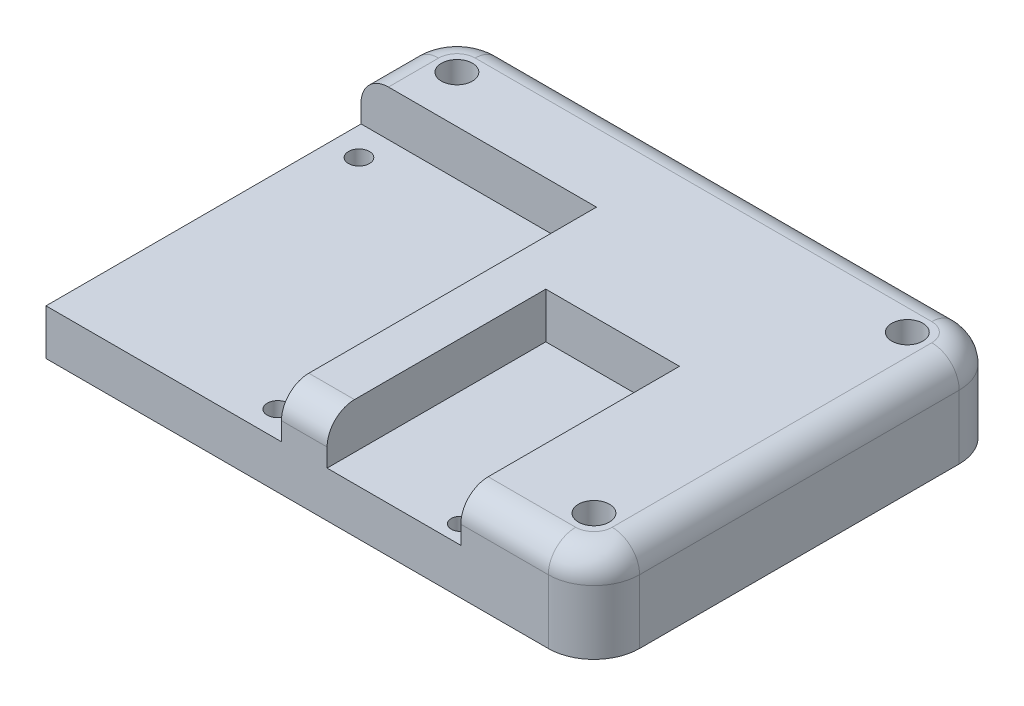
SolidWorks part; units mm, degrees
ref_plane "Front Plane" through (0, 0, 0) normal (0, 0, 1) x (1, 0, 0)
ref_plane "Top Plane" through (0, 0, 0) normal (0, 1, 0) x (1, 0, 0)
ref_plane "Right Plane" through (0, 0, 0) normal (1, 0, 0) x (0, 0, -1)
sketch "Sketch1" plane through (0, 0, 0) normal (0, 1, 0) x (1, 0, 0)
  line L1 (-39.1304, 20.7391) -> (20.8696, 20.7391)
  line L2 (-39.1304, 20.7391) -> (-39.1304, -24.2609)
  line L3 (-39.1304, -24.2609) -> (20.8696, -24.2609)
  line L4 (20.8696, 20.7391) -> (20.8696, -24.2609)
  dimension "D1" = 45
  dimension "D2" = 60
extrude "Boss-Extrude1" add sketch "Sketch1" along normal blind 10
sketch "Sketch2" plane through (0, 10, 0) normal (0, 1, 0) x (1, 0, 0)
  line L0 (-39.1304, -24.2609) -> (20.8696, -24.2609) construction
  line L1 (-13.3504, -24.2609) -> (-39.1304, -24.2609)
  line L2 (-13.3504, -24.2609) -> (-13.3504, 10.2391)
  line L3 (-13.3504, 10.2391) -> (-39.1304, 10.2391)
  line L4 (-39.1304, -24.2609) -> (-39.1304, 10.2391)
  line L5 (-39.1304, 20.7391) -> (-39.1304, -24.2609) construction
  dimension "D1" = 34.5
  dimension "D2" = 25.78
extrude "Cut-Extrude1" cut sketch "Sketch2" against normal blind 5
sketch "Sketch3" plane through (0, 5, 0) normal (0, 1, 0) x (1, 0, 0)
  line L0 (-13.3504, -24.2609) -> (-13.3504, 10.2391) construction
  line L1 (-39.1304, 10.2391) -> (-39.1304, -24.2609) construction
  line L2 (-39.1304, -24.2609) -> (-13.3504, -24.2609) construction
  line L3 (-13.3504, 10.2391) -> (-39.1304, 10.2391) construction
  circle A0 centre (-36.0604, 6.9391) radius 1.15
  circle A1 centre (-16.6404, -21.3709) radius 1.15
  dimension "D1" = 2.3
  dimension "D2" = 2.3
  dimension "D3" = 3.29
  dimension "D4" = 3.07
  dimension "D5" = 2.89
  dimension "D6" = 3.3
extrude "Cut-Extrude2" cut sketch "Sketch3" against normal up to next
sketch "Sketch4" plane through (0, 10, 0) normal (0, 1, 0) x (1, 0, 0)
  line L0 (-13.3504, -24.2609) -> (20.8696, -24.2609) construction
  line L1 (-8.3504, -24.2609) -> (6.2896, -24.2609)
  line L2 (-8.3504, -24.2609) -> (-8.3504, -0.3109)
  line L3 (-8.3504, -0.3109) -> (6.2896, -0.3109)
  line L4 (6.2896, -24.2609) -> (6.2896, -0.3109)
  line L5 (-13.3504, -24.2609) -> (-13.3504, 10.2391) construction
  dimension "D1" = 14.64
  dimension "D2" = 23.95
  dimension "D3" = 5
extrude "Cut-Extrude3" cut sketch "Sketch4" against normal blind 5
sketch "Sketch5" plane through (0, 5, 0) normal (0, 1, 0) x (1, 0, 0)
  line L0 (6.2896, -24.2609) -> (6.2896, -0.3109) construction
  line L1 (-8.3504, -24.2609) -> (6.2896, -24.2609) construction
  line L2 (6.2896, -0.3109) -> (-8.3504, -0.3109) construction
  circle A0 centre (4.2446, -2.3309) radius 1.015
  circle A1 centre (4.2396, -22.2459) radius 1.015
  point P4 (0, 0)
  dimension "D1" = 2.03
  dimension "D2" = 2.03
  dimension "D3" = 2.045
  dimension "D4" = 2.05
  dimension "D5" = 2.015
  dimension "D6" = 2.02
extrude "Cut-Extrude4" cut sketch "Sketch5" against normal up to next
fillet "Fillet1" radius 5 1 edges at (-39.1304, 5, -20.7391)
fillet "Fillet2" radius 5 1 edges at (20.8696, 5, -20.7391)
fillet "Fillet3" radius 5 1 edges at (20.8696, 5, 24.2609)
fillet "Fillet4" radius 3 8 edges at (-10.8504, 10, 24.2609) (-39.1304, 10, -12.9891) (-37.666, 10, -19.2747) (-9.1304, 10, -20.7391) (19.4051, 10, -19.2747) (20.8696, 10, 1.7609) (19.4051, 10, 22.7964) (11.0796, 10, 24.2609)
sketch "Sketch6" plane through (0, 10, 0) normal (0, 1, 0) x (1, 0, 0)
  line L0 (-34.1304, 20.7391) -> (15.8696, 20.7391) construction
  line L1 (-39.1304, 10.2391) -> (-39.1304, 15.7391) construction
  line L2 (20.8696, 15.7391) -> (20.8696, -19.2609) construction
  line L3 (15.8696, -24.2609) -> (6.2896, -24.2609) construction
  circle A0 centre (-33.7904, 15.3952) radius 1.7
  circle A1 centre (15.5296, 15.3991) radius 1.7
  circle A2 centre (15.5296, -18.9209) radius 1.7
  dimension "D1" = 3.4
  dimension "D2" = 3.4
  dimension "D3" = 3.4
  dimension "D4" = 5.3439
  dimension "D5" = 5.34
  dimension "D6" = 5.34
  dimension "D7" = 5.34
  dimension "D8" = 5.34
  dimension "D9" = 5.34
extrude "Cut-Extrude5" cut sketch "Sketch6" against normal up to next
equation "\"ESP_HOLE\"=2.3"
equation "\"D1@Sketch3\"=\"ESP_HOLE\""
equation "\"PT_HOLE\"=2.03"
equation "\"D1@Sketch5\"=\"PT_HOLE\""
equation "\"Mount\"=3.4"
equation "\"D1@Sketch6\"=\"Mount\""
equation "\"M_OFF\"=5.34394"
equation "\"D4@Sketch6\"=\"M_OFF\""
